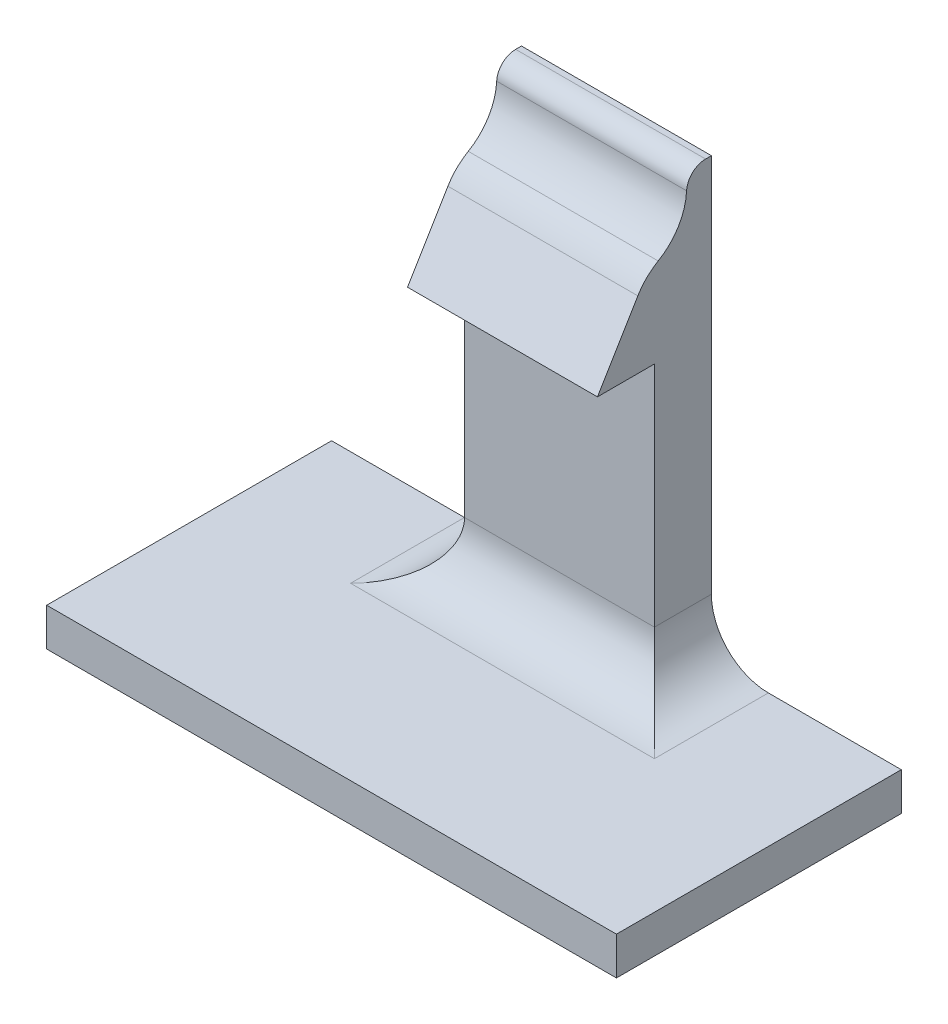
SolidWorks part; units mm, degrees
ref_plane "Спереди" through (0, 0, 0) normal (0, 0, 1) x (1, 0, 0)
ref_plane "Сверху" through (0, 0, 0) normal (0, 1, 0) x (1, 0, 0)
ref_plane "Справа" through (0, 0, 0) normal (1, 0, 0) x (0, 0, -1)
sketch "Эскиз1" plane through (0, 0, 0) normal (0, 1, 0) x (1, 0, 0)
  line L1 (-15, 7.5) -> (15, 7.5)
  line L2 (-15, 7.5) -> (-15, -7.5)
  line L3 (-15, -7.5) -> (15, -7.5)
  line L4 (15, 7.5) -> (15, -7.5)
  line L5 (-15, 7.5) -> (15, -7.5) construction
  line L6 (-15, -7.5) -> (15, 7.5) construction
  point P0 (0, 0)
  dimension "D1" = 30
  dimension "D2" = 15
extrude "Бобышка-Вытянуть1" add sketch "Эскиз1" along normal blind 2
sketch "Эскиз2" plane through (0, 2, 0) normal (0, 1, 0) x (1, 0, 0)
  line L0 (15, 7.5) -> (-15, 7.5) construction
  line L1 (-5, 7.5) -> (5, 7.5)
  line L2 (-5, 7.5) -> (-5, 4.5)
  line L3 (-5, 4.5) -> (5, 4.5)
  line L4 (5, 7.5) -> (5, 4.5)
  point P6 (0, 7.5)
  dimension "D1" = 10
  dimension "D2" = 3
extrude "Бобышка-Вытянуть2" add sketch "Эскиз2" along normal blind 20
sketch "Эскиз3" plane through (-5, 0, 0) normal (-1, 0, 0) x (0, 0, 1)
  line L0 (-4.5, 22) -> (-1.5, 17)
  line L1 (-1.5, 17) -> (-4.5, 17)
  line L2 (-4.5, 22) -> (-4.5, 2) construction
  line L3 (-4.5, 17) -> (-4.5, 22)
  dimension "D1" = 3
  dimension "D2" = 5
extrude "Бобышка-Вытянуть3" add sketch "Эскиз3" against normal up to surface (10 mm away) up to face at (5, 12, -6)
fillet "Скругление2" radius 3 1 edges at (0, 22, -4.5)
fillet "Скругление3" radius 3 1 edges at (0, 2, -4.5)
fillet "Скругление4" radius 3 2 edges at (-5, 2, -4.5) (5, 2, -4.5)
sketch "Эскиз5" plane through (0, 22, 0) normal (0, 1, 0) x (1, 0, 0)
  line L0 (5, 4.5) -> (5, 7.5) construction
  line L1 (-5, 7.5) -> (5, 7.5)
  line L2 (-5, 7.5) -> (-5, 6.1986)
  line L3 (-5, 6.1986) -> (5, 6.1986)
  line L4 (5, 7.5) -> (5, 6.1986)
  line L5 (5, 6.1986) -> (5, 7.5) construction
extrude "Бобышка-Вытянуть4" add sketch "Эскиз5" along normal blind 3
fillet "Скругление5" radius 3 1 edges at (0, 22, -6.1986)
fillet "Скругление6" radius 1 1 edges at (0, 25, -6.1986)
